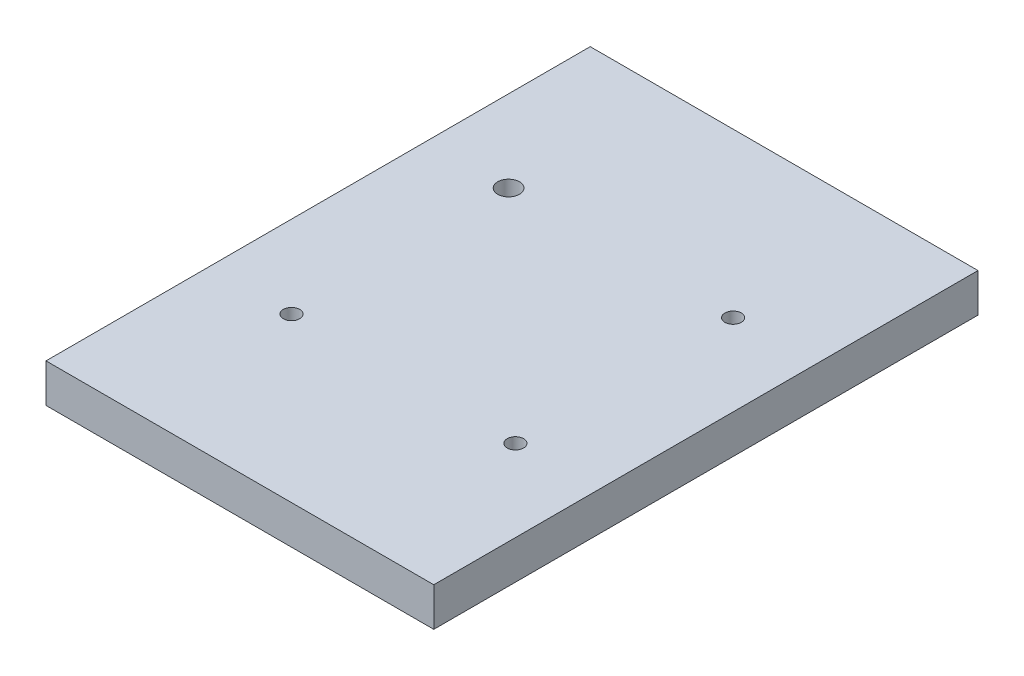
SolidWorks part; units mm, degrees
ref_plane "Front Plane" through (0, 0, 0) normal (0, 0, 1) x (1, 0, 0)
ref_plane "Top Plane" through (0, 0, 0) normal (0, 1, 0) x (1, 0, 0)
ref_plane "Right Plane" through (0, 0, 0) normal (1, 0, 0) x (0, 0, -1)
sketch "Sketch1" plane through (0, 0, 0.7489) normal (0, 1, 0) x (1, 0, 0)
  line L0 (0, 43) -> (0, 33)
  line L5 (-45.4667, -37.5525) -> (25.7862, -37.5525)
  line L6 (-45.4667, -37.5525) -> (-45.4667, -137.5525)
  line L7 (-45.4667, -137.5525) -> (25.7862, -137.5525)
  line L8 (25.7862, -37.5525) -> (25.7862, -137.5525)
  line L9 (0, -33) -> (0, -43)
  dimension "D1" = 100
extrude "Boss-Extrude1" add sketch "Sketch1" along normal mid plane 7.1
sketch "Sketch6" plane through (0, 3.55, 0.7489) normal (0, 1, 0) x (1, 0, 0)
  line L3 (25.7862, -33) -> (25.7862, -107.9999) construction
  line L9 (-45.4667, -37.5525) -> (25.7862, -37.5525) construction
  circle A0 centre (10.7862, -67.5525) radius 1.5
  circle A3 centre (-30.4667, -67.5525) radius 2
  circle A4 centre (10.7862, -107.5525) radius 1.5
  circle A5 centre (-30.3587, -107.5525) radius 1.5
  dimension "D1" = 3
  dimension "D2" = 15
  dimension "D3" = 30
  dimension "D5" = 3
  dimension "D11" = 4
extrude "Cut-Extrude11" cut sketch "Sketch6" against normal through all
